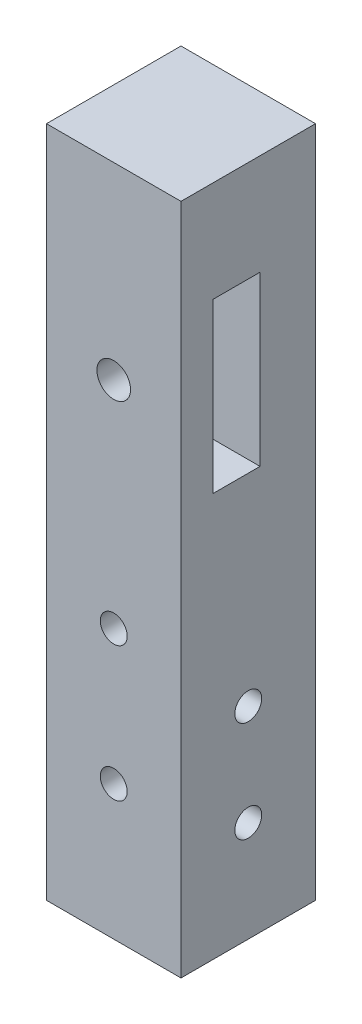
SolidWorks part; units mm, degrees
ref_plane "Front Plane" through (0, 0, 0) normal (0, 0, 1) x (1, 0, 0)
ref_plane "Top Plane" through (0, 0, 0) normal (0, 1, 0) x (1, 0, 0)
ref_plane "Right Plane" through (0, 0, 0) normal (1, 0, 0) x (0, 0, -1)
sketch "Sketch1" plane through (0, 0, 0) normal (0, 0, 1) x (1, 0, 0)
  line L1 (-59.4675, 56.9527) -> (16.4325, 56.9527)
  line L2 (-59.4675, 56.9527) -> (-59.4675, -43.0473)
  line L3 (-59.4675, -43.0473) -> (16.4325, -43.0473)
  line L4 (16.4325, 56.9527) -> (16.4325, -43.0473)
  dimension "D1" = 100
  dimension "D2" = 75.9
extrude "Boss-Extrude1" add sketch "Sketch1" along normal blind 20
sketch "Sketch2" plane through (0, 0, 20) normal (0, 0, 1) x (1, 0, 0)
  line L0 (-21.5175, 56.9527) -> (-21.5175, 28.9527) construction
  line L1 (16.4325, 56.9527) -> (-59.4675, 56.9527) construction
  line L2 (-21.5175, 28.9527) -> (-21.5175, -43.0473) construction
  line L3 (-59.4675, -43.0473) -> (16.4325, -43.0473) construction
  circle A0 centre (-21.5175, 28.9527) radius 2.5
  dimension "D2" = 5
  dimension "D1" = 72
extrude "Cut-Extrude1" cut sketch "Sketch2" against normal through all
sketch "Sketch3" plane through (0, 0, 20) normal (0, 0, 1) x (1, 0, 0)
  line L0 (-59.4675, -43.0473) -> (16.4325, -43.0473) construction
  line L1 (-59.4675, 56.9527) -> (-31.5175, 56.9527)
  line L2 (-59.4675, 56.9527) -> (-59.4675, -43.0473)
  line L3 (-59.4675, -43.0473) -> (-31.5175, -43.0473)
  line L4 (-31.5175, 56.9527) -> (-31.5175, -43.0473)
  line L5 (-21.5175, 56.9527) -> (-21.5175, -43.0473) construction
  line L6 (16.4325, 56.9527) -> (-11.5175, 56.9527)
  line L7 (16.4325, 56.9527) -> (16.4325, -43.0473)
  line L8 (16.4325, -43.0473) -> (-11.5175, -43.0473)
  line L9 (-11.5175, 56.9527) -> (-11.5175, -43.0473)
  line L10 (16.4325, 56.9527) -> (-59.4675, 56.9527) construction
  dimension "D1" = 20
  dimension "D2" = 10
extrude "Cut-Extrude2" cut sketch "Sketch3" against normal through all
sketch "Sketch4" plane through (-11.5175, 0, 0) normal (1, 0, 0) x (0, 0, -1)
  line L1 (-15.25, 41.9527) -> (-8.25, 41.9527)
  line L2 (-15.25, 41.9527) -> (-15.25, 16.9527)
  line L3 (-15.25, 16.9527) -> (-8.25, 16.9527)
  line L4 (-8.25, 41.9527) -> (-8.25, 16.9527)
  line L5 (0, 56.9527) -> (0, -43.0473) construction
  line L6 (0, 56.9527) -> (-20, 56.9527) construction
  dimension "D1" = 8.25
  dimension "D2" = 7
  dimension "D3" = 25
  dimension "D4" = 15
extrude "Cut-Extrude3" cut sketch "Sketch4" against normal blind 41
sketch "Sketch5" plane through (0, 0, 20) normal (0, 0, 1) x (1, 0, 0)
  line L0 (-21.5175, -43.0473) -> (-21.5175, -3.0473) construction
  line L1 (-31.5175, -43.0473) -> (-11.5175, -43.0473) construction
  circle A0 centre (-21.5175, -3.0473) radius 2
  circle A1 centre (-21.5175, -23.0473) radius 2
  dimension "D1" = 4
  dimension "D2" = 40
extrude "Cut-Extrude4" cut sketch "Sketch5" against normal through all
sketch "Sketch6" plane through (-11.5175, 0, 0) normal (1, 0, 0) x (0, 0, -1)
  line L0 (-10, -43.0473) -> (-10, -13.0473) construction
  line L1 (0, -43.0473) -> (-20, -43.0473) construction
  circle A0 centre (-10, -13.0473) radius 2
  circle A1 centre (-10, -28.0473) radius 2
  dimension "D2" = 4
  dimension "D1" = 30
extrude "Cut-Extrude5" cut sketch "Sketch6" against normal through all
